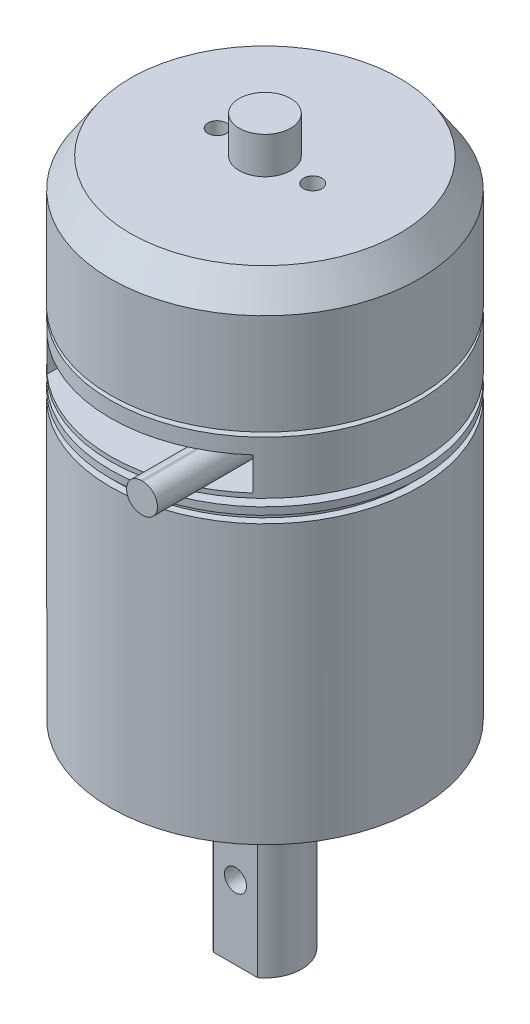
SolidWorks part; units mm, degrees
material "6061-O (SS)"
ref_plane "前视基准面" through (0, 0, 0) normal (0, 0, 1) x (1, 0, 0)
ref_plane "上视基准面" through (0, 0, 0) normal (0, 1, 0) x (1, 0, 0)
ref_plane "右视基准面" through (0, 0, 0) normal (1, 0, 0) x (0, 0, -1)
sketch "草图1" plane through (0, 0, 0) normal (0, 0, 1) x (1, 0, 0)
  line L0 (0, 0) -> (4.1, 0)
  line L1 (4.1, 0) -> (4.1, 6.7)
  line L2 (4.1, 6.7) -> (13.4, 6.7)
  line L3 (13.4, 6.7) -> (13.4, 8.7)
  line L4 (13.4, 8.7) -> (21, 8.7)
  line L5 (21, 8.7) -> (21, 10.2)
  line L6 (21, 10.2) -> (20, 10.2)
  line L7 (20, 10.2) -> (20, 11.2)
  line L8 (20, 11.2) -> (21, 11.2)
  line L9 (21, 11.2) -> (21, 12.2)
  line L10 (21, 12.2) -> (10, 12.2)
  line L11 (10, 12.2) -> (10, 13.2)
  line L12 (10, 13.2) -> (21, 13.2)
  line L13 (21, 13.2) -> (21, 20.4)
  line L14 (21, 20.4) -> (5, 20.4)
  line L15 (5, 20.4) -> (5, 21)
  line L16 (5, 21) -> (21, 21)
  line L17 (21, 21) -> (21, 34.7)
  line L18 (21, 34.7) -> (18.3, 38.7)
  line L19 (18.3, 38.7) -> (3.5, 38.7)
  line L20 (3.5, 38.7) -> (3.5, 43.7)
  line L21 (3.5, 43.7) -> (0, 43.7)
  line L22 (0, 43.7) -> (0, 0) construction
  line L23 (0, 0) -> (0, 43.7)
  dimension "D1" = 8.2
  dimension "D2" = 26.8
  dimension "D3" = 42
  dimension "D4" = 10
  dimension "D5" = 1.5
  dimension "D6" = 1
  dimension "D7" = 1
  dimension "D8" = 20
  dimension "D9" = 1
  dimension "D10" = 7.2
  dimension "D11" = 0.6
  dimension "D12" = 13.7
  dimension "D13" = 5
  dimension "D14" = 2
  dimension "D15" = 6.7
  dimension "D16" = 1
  dimension "D17" = 7
  dimension "D18" = 36.6
  dimension "D19" = 4
  dimension "D20" = 30
revolve "旋转1" add sketch "草图1" angle 360 about L22
ref_plane "基准面1" through (0, 0, 21) normal (0, 0, 1) x (1, 0, 0)
sketch "草图2" plane through (0, 0, 21) normal (0, 0, 1) x (1, 0, 0)
  line L1 (-14, 18.3) -> (14, 18.3)
  line L2 (-14, 18.3) -> (-14, 13.8)
  line L3 (-14, 13.8) -> (14, 13.8)
  line L4 (14, 18.3) -> (14, 13.8)
  line L5 (-14, 18.3) -> (14, 13.8) construction
  line L6 (-14, 13.8) -> (14, 18.3) construction
  line L7 (-21, 13.2) -> (21, 13.2) construction
  point P0 (0, 16.05)
  dimension "D1" = 28
  dimension "D2" = 4.5
  dimension "D3" = 0.6
extrude "切除-拉伸1" cut sketch "草图2" against normal blind 10
sketch "草图3" plane through (0, 0, 11) normal (0, 0, 1) x (1, 0, 0)
  line L0 (9.1851, 16.0532) -> (9.3851, 16.0532) construction
  line L1 (9.1851, 18.0532) -> (9.3851, 18.0532)
  line L2 (9.1851, 14.0532) -> (9.3851, 14.0532)
  arc A0 (9.1851, 18.0532) -> (9.1851, 14.0532) centre (9.1851, 16.0532) ccw
  arc A1 (9.3851, 14.0532) -> (9.3851, 18.0532) centre (9.3851, 16.0532) ccw
  point P2 (9.2851, 16.0532)
  dimension "D1" = 4
  dimension "D2" = 0.2
extrude "凸台-拉伸1" add sketch "草图3" along normal blind 15
hole_wizard "M3 螺纹孔1" positions "草图5" profile "草图6" tap size "M3" standard "GB"
sketch "草图5" plane through (0, 38.7, 0) normal (0, 1, 0) x (1, 0, 0)
  line L0 (0, 0) -> (0, 8.0606) construction
  point P0 (-6.5, 0)
  point P2 (6.5, 0)
  dimension "D1" = 13
sketch "草图6" plane through (-6.5, 38.7, 0) normal (1, 0, 0) x (0, 0, 1)
  line L0 (0, 0) -> (0, 4.7511)
  line L1 (0, 4.7511) -> (1.25, 4)
  line L2 (1.25, 4) -> (1.25, 0)
  line L5 (1.25, 0) -> (0, 0)
  line L10 (0, 4.7511) -> (-1.25, 4) construction
  line L11 (0, -6.35) -> (0, 107.95) construction
  dimension "螺纹孔钻头直径" = 2.5
  dimension "螺纹孔钻头深度" = 4
  dimension "导头角度" = 118
cosmetic thread "孔螺蚊线1" parameters "D1"=4, "D2"=3
cosmetic thread "孔螺蚊线2" parameters "D1"=4, "D2"=3
sketch "草图7" plane through (0, 0, 0) normal (0, 0, 1) x (1, 0, 0)
  line L0 (0, 8.7) -> (0, -54.6) construction
  line L1 (-13.4, 8.7) -> (13.4, 8.7) construction
  line L2 (0, -54.6) -> (5, -54.6)
  line L3 (5, -54.6) -> (5, -30.5)
  line L4 (5, -30.5) -> (8.275, -30.5)
  line L5 (13, -29.6) -> (13, -27.6)
  line L6 (13, -27.6) -> (21, -27.6)
  line L7 (21, -27.6) -> (21, 8.7)
  line L8 (-21, 8.7) -> (21, 8.7) construction
  line L9 (21, 8.7) -> (0, 8.7)
  line L10 (18.3, 38.7) -> (-18.3, 38.7) construction
  line L11 (13, -29.6) -> (8.275, -29.6)
  line L12 (8.275, -29.6) -> (8.275, -30.5)
  line L13 (0, 8.7) -> (0, -54.6)
  dimension "D1" = 66.3
  dimension "D2" = 2
  dimension "D3" = 0.9
  dimension "D4" = 27
  dimension "D5" = 26
  dimension "D6" = 10
  dimension "D7" = 16.55
revolve "旋转2" add sketch "草图7" angle 360 about L0
sketch "草图8" plane through (0, -54.6, 0) normal (0, -1, 0) x (1, 0, 0)
  line L0 (-3, 4) -> (3, 4)
  circle A0 centre (0, 0) radius 5 construction
  circle A1 centre (0, 0) radius 5 construction
  arc A2 (3, 4) -> (-3, 4) centre (0, 0) ccw
  dimension "D1" = 4
extrude "切除-拉伸2" cut sketch "草图8" against normal blind 20
hole_wizard "M4 螺纹孔1" positions "草图10" profile "草图9" tap size "M4" standard "GB"
sketch "草图10" plane through (0, -27.6, 0) normal (0, -1, 0) x (-1, 0, 0)
  circle A0 centre (0, 0) radius 17.5
  point P5 (0, -17.5)
  point P7 (-17.5, 0)
  point P9 (0, 17.5)
  point P11 (17.5, 0)
  dimension "D1" = 35
sketch "草图9" plane through (0, -27.6, 17.5) normal (1, 0, 0) x (0, 0, -1)
  line L0 (0, 0) -> (0, 11.0914)
  line L1 (0, 11.0914) -> (1.65, 10.1)
  line L2 (1.65, 10.1) -> (1.65, 0)
  line L5 (1.65, 0) -> (0, 0)
  line L10 (0, 11.0914) -> (-1.65, 10.1) construction
  line L11 (0, -6.35) -> (0, 107.95) construction
  dimension "螺纹孔钻头直径" = 3.3
  dimension "螺纹孔钻头深度" = 10.1
  dimension "导头角度" = 118
cosmetic thread "孔螺蚊线3" parameters "D1"=8, "D2"=4
cosmetic thread "孔螺蚊线4" parameters "D1"=8, "D2"=4
cosmetic thread "孔螺蚊线5" parameters "D1"=8, "D2"=4
cosmetic thread "孔螺蚊线6" parameters "D1"=8, "D2"=4
sketch "草图11" plane through (0, 0, 4) normal (0, 0, 1) x (1, 0, 0)
  line L0 (0, -54.6) -> (0, -44.6) construction
  line L1 (0, -54.6) -> (0, -34.6) construction
  line L2 (-3, -54.6) -> (3, -54.6) construction
  circle A0 centre (0, -44.6) radius 1.5
  dimension "D2" = 3
  dimension "D1" = 10
extrude "切除-拉伸3" cut sketch "草图11" against normal through all both and the other way through all
